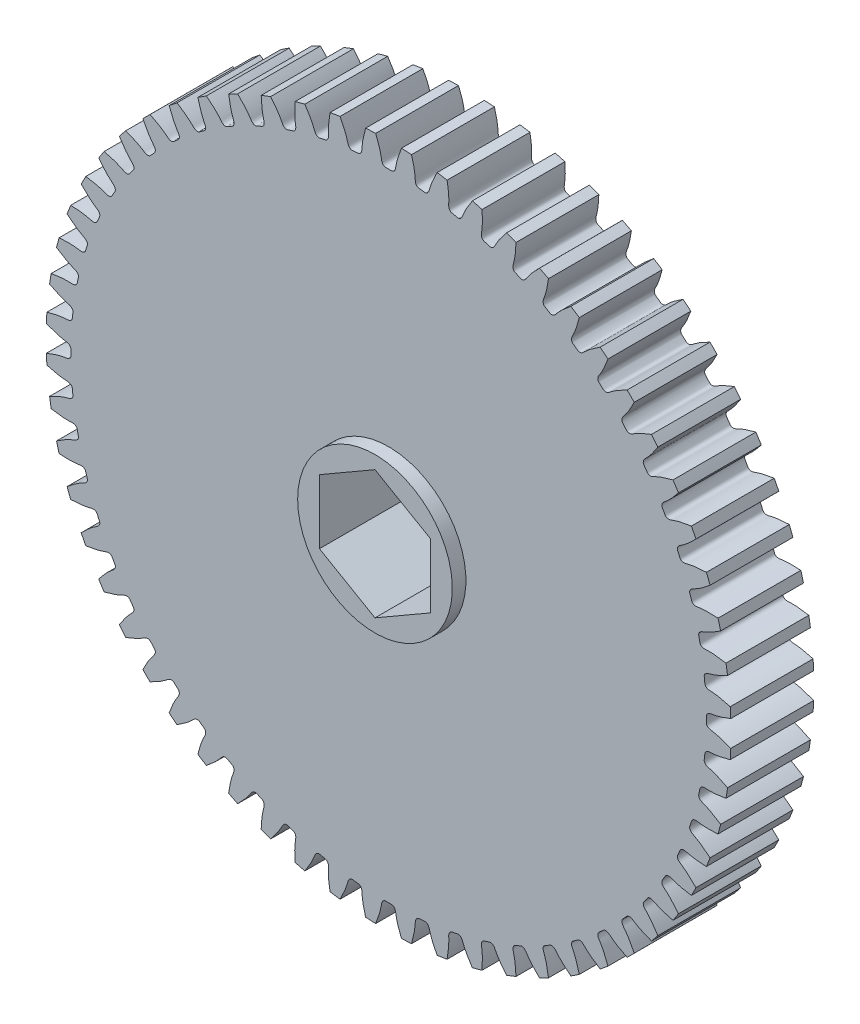
SolidWorks part; units mm, degrees
material "7075-T6 (SN)"
ref_plane "Front Plane" through (0, 0, 0) normal (0, 0, 1) x (1, 0, 0)
ref_plane "Top Plane" through (0, 0, 0) normal (0, 1, 0) x (1, 0, 0)
ref_plane "Right Plane" through (0, 0, 0) normal (1, 0, 0) x (0, 0, -1)
ref_plane "Plane1" through (0, 0, 4.7625) normal (0, 0, 1) x (1, 0, 0)
sketch "Sketch1" plane through (0, 0, 4.7625) normal (0, 0, 1) x (1, 0, 0)
  arc A0 (39.3421, 1.4811) -> (39.2814, 2.6394) centre (0, 0) ccw
  arc A1 (38.9718, 5.5854) -> (38.7904, 6.7309) centre (0, 0) ccw
  arc A2 (38.1745, 9.6285) -> (37.8743, 10.7487) centre (0, 0) ccw
  arc A3 (36.9589, 13.566) -> (36.5433, 14.6488) centre (0, 0) ccw
  arc A4 (35.3384, 17.355) -> (34.8118, 18.3884) centre (0, 0) ccw
  arc A5 (33.3307, 20.9538) -> (32.699, 21.9265) centre (0, 0) ccw
  arc A6 (30.9579, 24.323) -> (30.228, 25.2243) centre (0, 0) ccw
  arc A7 (28.2458, 27.4257) -> (27.4257, 28.2458) centre (0, 0) ccw
  arc A8 (25.2243, 30.228) -> (24.323, 30.9579) centre (0, 0) ccw
  arc A9 (21.9265, 32.699) -> (20.9538, 33.3307) centre (0, 0) ccw
  arc A10 (18.3884, 34.8118) -> (17.355, 35.3384) centre (0, 0) ccw
  arc A11 (14.6488, 36.5433) -> (13.566, 36.9589) centre (0, 0) ccw
  arc A12 (10.7487, 37.8743) -> (9.6285, 38.1745) centre (0, 0) ccw
  arc A13 (6.7309, 38.7904) -> (5.5854, 38.9718) centre (0, 0) ccw
  arc A14 (2.6394, 39.2814) -> (1.4811, 39.3421) centre (0, 0) ccw
  arc A15 (-1.4811, 39.3421) -> (-2.6394, 39.2814) centre (0, 0) ccw
  arc A16 (-5.5854, 38.9718) -> (-6.7309, 38.7904) centre (0, 0) ccw
  arc A17 (-9.6285, 38.1745) -> (-10.7487, 37.8743) centre (0, 0) ccw
  arc A18 (-13.566, 36.9589) -> (-14.6488, 36.5433) centre (0, 0) ccw
  arc A19 (-17.355, 35.3384) -> (-18.3884, 34.8118) centre (0, 0) ccw
  arc A20 (-20.9538, 33.3307) -> (-21.9265, 32.699) centre (0, 0) ccw
  arc A21 (-24.323, 30.9579) -> (-25.2243, 30.228) centre (0, 0) ccw
  arc A22 (-27.4257, 28.2458) -> (-28.2458, 27.4257) centre (0, 0) ccw
  arc A23 (-30.228, 25.2243) -> (-30.9579, 24.323) centre (0, 0) ccw
  arc A24 (-32.699, 21.9265) -> (-33.3307, 20.9538) centre (0, 0) ccw
  arc A25 (-34.8118, 18.3884) -> (-35.3384, 17.355) centre (0, 0) ccw
  arc A26 (-36.5433, 14.6488) -> (-36.9589, 13.566) centre (0, 0) ccw
  arc A27 (-37.8743, 10.7487) -> (-38.1745, 9.6285) centre (0, 0) ccw
  arc A28 (-38.7904, 6.7309) -> (-38.9718, 5.5854) centre (0, 0) ccw
  arc A29 (-39.2814, 2.6394) -> (-39.3421, 1.4811) centre (0, 0) ccw
  arc A30 (-39.3421, -1.4811) -> (-39.2814, -2.6394) centre (0, 0) ccw
  arc A31 (-38.9718, -5.5854) -> (-38.7904, -6.7309) centre (0, 0) ccw
  arc A32 (-38.1745, -9.6285) -> (-37.8743, -10.7487) centre (0, 0) ccw
  arc A33 (-36.9589, -13.566) -> (-36.5433, -14.6488) centre (0, 0) ccw
  arc A34 (-35.3384, -17.355) -> (-34.8118, -18.3884) centre (0, 0) ccw
  arc A35 (-33.3307, -20.9538) -> (-32.699, -21.9265) centre (0, 0) ccw
  arc A36 (-30.9579, -24.323) -> (-30.228, -25.2243) centre (0, 0) ccw
  arc A37 (-28.2458, -27.4257) -> (-27.4257, -28.2458) centre (0, 0) ccw
  arc A38 (-25.2243, -30.228) -> (-24.323, -30.9579) centre (0, 0) ccw
  arc A39 (-21.9265, -32.699) -> (-20.9538, -33.3307) centre (0, 0) ccw
  arc A40 (-18.3884, -34.8118) -> (-17.355, -35.3384) centre (0, 0) ccw
  arc A41 (-14.6488, -36.5433) -> (-13.566, -36.9589) centre (0, 0) ccw
  arc A42 (-10.7487, -37.8743) -> (-9.6285, -38.1745) centre (0, 0) ccw
  arc A43 (-6.7309, -38.7904) -> (-5.5854, -38.9718) centre (0, 0) ccw
  arc A44 (-2.6394, -39.2814) -> (-1.4811, -39.3421) centre (0, 0) ccw
  arc A45 (1.4811, -39.3421) -> (2.6394, -39.2814) centre (0, 0) ccw
  arc A46 (5.5854, -38.9718) -> (6.7309, -38.7904) centre (0, 0) ccw
  arc A47 (9.6285, -38.1745) -> (10.7487, -37.8743) centre (0, 0) ccw
  arc A48 (13.566, -36.9589) -> (14.6488, -36.5433) centre (0, 0) ccw
  arc A49 (17.355, -35.3384) -> (18.3884, -34.8118) centre (0, 0) ccw
  arc A50 (20.9538, -33.3307) -> (21.9265, -32.699) centre (0, 0) ccw
  arc A51 (24.323, -30.9579) -> (25.2243, -30.228) centre (0, 0) ccw
  arc A52 (27.4257, -28.2458) -> (28.2458, -27.4257) centre (0, 0) ccw
  arc A53 (30.228, -25.2243) -> (30.9579, -24.323) centre (0, 0) ccw
  arc A54 (32.699, -21.9265) -> (33.3307, -20.9538) centre (0, 0) ccw
  arc A55 (34.8118, -18.3884) -> (35.3384, -17.355) centre (0, 0) ccw
  arc A56 (36.5433, -14.6488) -> (36.9589, -13.566) centre (0, 0) ccw
  arc A57 (37.8743, -10.7487) -> (38.1745, -9.6285) centre (0, 0) ccw
  arc A58 (38.7904, -6.7309) -> (38.9718, -5.5854) centre (0, 0) ccw
  arc A59 (39.2814, -2.6394) -> (39.3421, -1.4811) centre (0, 0) ccw
  spline S0 degree 3 number of poles 79 (39.3421, 1.4811) -> (39.3421, -1.4811)
  spline S1 degree 3 number of poles 79 (38.9718, 5.5854) -> (39.2814, 2.6394)
  spline S2 degree 3 number of poles 79 (38.1745, 9.6285) -> (38.7904, 6.7309)
  spline S3 degree 3 number of poles 79 (36.9589, 13.566) -> (37.8743, 10.7487)
  spline S4 degree 3 number of poles 79 (35.3384, 17.355) -> (36.5433, 14.6488)
  spline S5 degree 3 number of poles 79 (33.3307, 20.9538) -> (34.8118, 18.3884)
  spline S6 degree 3 number of poles 79 (30.9579, 24.323) -> (32.699, 21.9265)
  spline S7 degree 3 number of poles 79 (28.2458, 27.4257) -> (30.228, 25.2243)
  spline S8 degree 3 number of poles 79 (25.2243, 30.228) -> (27.4257, 28.2458)
  spline S9 degree 3 number of poles 79 (21.9265, 32.699) -> (24.323, 30.9579)
  spline S10 degree 3 number of poles 79 (18.3884, 34.8118) -> (20.9538, 33.3307)
  spline S11 degree 3 number of poles 79 (14.6488, 36.5433) -> (17.355, 35.3384)
  spline S12 degree 3 number of poles 79 (10.7487, 37.8743) -> (13.566, 36.9589)
  spline S13 degree 3 number of poles 79 (6.7309, 38.7904) -> (9.6285, 38.1745)
  spline S14 degree 3 number of poles 79 (2.6394, 39.2814) -> (5.5854, 38.9718)
  spline S15 degree 3 number of poles 79 (-1.4811, 39.3421) -> (1.4811, 39.3421)
  spline S16 degree 3 number of poles 79 (-5.5854, 38.9718) -> (-2.6394, 39.2814)
  spline S17 degree 3 number of poles 79 (-9.6285, 38.1745) -> (-6.7309, 38.7904)
  spline S18 degree 3 number of poles 79 (-13.566, 36.9589) -> (-10.7487, 37.8743)
  spline S19 degree 3 number of poles 79 (-17.355, 35.3384) -> (-14.6488, 36.5433)
  spline S20 degree 3 number of poles 79 (-20.9538, 33.3307) -> (-18.3884, 34.8118)
  spline S21 degree 3 number of poles 79 (-24.323, 30.9579) -> (-21.9265, 32.699)
  spline S22 degree 3 number of poles 79 (-27.4257, 28.2458) -> (-25.2243, 30.228)
  spline S23 degree 3 number of poles 79 (-30.228, 25.2243) -> (-28.2458, 27.4257)
  spline S24 degree 3 number of poles 79 (-32.699, 21.9265) -> (-30.9579, 24.323)
  spline S25 degree 3 number of poles 79 (-34.8118, 18.3884) -> (-33.3307, 20.9538)
  spline S26 degree 3 number of poles 79 (-36.5433, 14.6488) -> (-35.3384, 17.355)
  spline S27 degree 3 number of poles 79 (-37.8743, 10.7487) -> (-36.9589, 13.566)
  spline S28 degree 3 number of poles 79 (-38.7904, 6.7309) -> (-38.1745, 9.6285)
  spline S29 degree 3 number of poles 79 (-39.2814, 2.6394) -> (-38.9718, 5.5854)
  spline S30 degree 3 number of poles 79 (-39.3421, -1.4811) -> (-39.3421, 1.4811)
  spline S31 degree 3 number of poles 79 (-38.9718, -5.5854) -> (-39.2814, -2.6394)
  spline S32 degree 3 number of poles 79 (-38.1745, -9.6285) -> (-38.7904, -6.7309)
  spline S33 degree 3 number of poles 79 (-36.9589, -13.566) -> (-37.8743, -10.7487)
  spline S34 degree 3 number of poles 79 (-35.3384, -17.355) -> (-36.5433, -14.6488)
  spline S35 degree 3 number of poles 79 (-33.3307, -20.9538) -> (-34.8118, -18.3884)
  spline S36 degree 3 number of poles 79 (-30.9579, -24.323) -> (-32.699, -21.9265)
  spline S37 degree 3 number of poles 79 (-28.2458, -27.4257) -> (-30.228, -25.2243)
  spline S38 degree 3 number of poles 79 (-25.2243, -30.228) -> (-27.4257, -28.2458)
  spline S39 degree 3 number of poles 79 (-21.9265, -32.699) -> (-24.323, -30.9579)
  spline S40 degree 3 number of poles 79 (-18.3884, -34.8118) -> (-20.9538, -33.3307)
  spline S41 degree 3 number of poles 79 (-14.6488, -36.5433) -> (-17.355, -35.3384)
  spline S42 degree 3 number of poles 79 (-10.7487, -37.8743) -> (-13.566, -36.9589)
  spline S43 degree 3 number of poles 79 (-6.7309, -38.7904) -> (-9.6285, -38.1745)
  spline S44 degree 3 number of poles 79 (-2.6394, -39.2814) -> (-5.5854, -38.9718)
  spline S45 degree 3 number of poles 79 (1.4811, -39.3421) -> (-1.4811, -39.3421)
  spline S46 degree 3 number of poles 79 (5.5854, -38.9718) -> (2.6394, -39.2814)
  spline S47 degree 3 number of poles 79 (9.6285, -38.1745) -> (6.7309, -38.7904)
  spline S48 degree 3 number of poles 79 (13.566, -36.9589) -> (10.7487, -37.8743)
  spline S49 degree 3 number of poles 79 (17.355, -35.3384) -> (14.6488, -36.5433)
  spline S50 degree 3 number of poles 79 (20.9538, -33.3307) -> (18.3884, -34.8118)
  spline S51 degree 3 number of poles 79 (24.323, -30.9579) -> (21.9265, -32.699)
  spline S52 degree 3 number of poles 79 (27.4257, -28.2458) -> (25.2243, -30.228)
  spline S53 degree 3 number of poles 79 (30.228, -25.2243) -> (28.2458, -27.4257)
  spline S54 degree 3 number of poles 79 (32.699, -21.9265) -> (30.9579, -24.323)
  spline S55 degree 3 number of poles 79 (34.8118, -18.3884) -> (33.3307, -20.9538)
  spline S56 degree 3 number of poles 79 (36.5433, -14.6488) -> (35.3384, -17.355)
  spline S57 degree 3 number of poles 79 (37.8743, -10.7487) -> (36.9589, -13.566)
  spline S58 degree 3 number of poles 79 (38.7904, -6.7309) -> (38.1745, -9.6285)
  spline S59 degree 3 number of poles 79 (39.2814, -2.6394) -> (38.9718, -5.5854)
extrude "Boss-Extrude1" add sketch "Sketch1" against normal blind 9.525
sketch "Sketch2" plane through (0, 0, 4.7625) normal (0, 0, 1) x (1, 0, 0)
  circle A0 centre (0, 0) radius 8.89
extrude "Boss-Extrude2" add sketch "Sketch2" along normal blind 1.5621
sketch "Sketch3" plane through (0, 0, -4.7625) normal (0, 0, -1) x (-1, 0, 0)
  circle A0 centre (0, 0) radius 8.89
extrude "Boss-Extrude3" add sketch "Sketch3" along normal blind 1.5621
sketch "Sketch4" plane through (0, 0, -6.3246) normal (0, 0, -1) x (-1, 0, 0)
  line L0 (6.3881, 3.6882) -> (0, 7.3763)
  line L1 (0, 7.3763) -> (-6.3881, 3.6882)
  line L2 (-6.3881, 3.6882) -> (-6.3881, -3.6882)
  line L3 (-6.3881, -3.6882) -> (0, -7.3763)
  line L4 (0, -7.3763) -> (6.3881, -3.6882)
  line L5 (6.3881, -3.6882) -> (6.3881, 3.6882)
extrude "Cut-Extrude1" cut sketch "Sketch4" against normal through all
